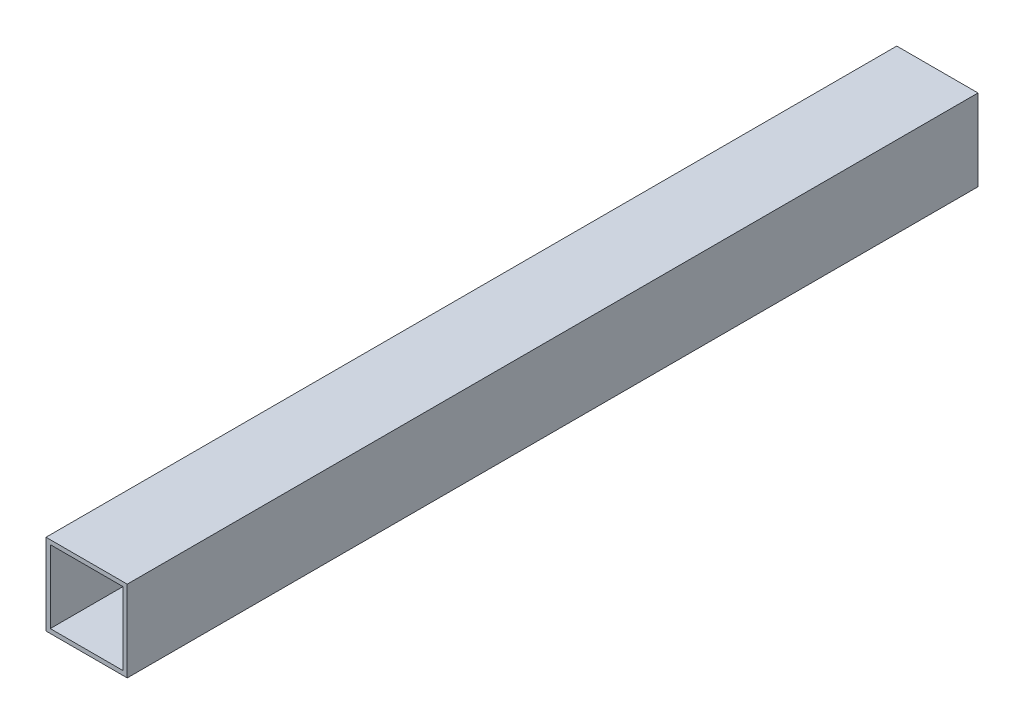
SolidWorks part; units mm, degrees
ref_plane "Front Plane" through (0, 0, 0) normal (0, 0, 1) x (1, 0, 0)
ref_plane "Top Plane" through (0, 0, 0) normal (0, 1, 0) x (1, 0, 0)
ref_plane "Right Plane" through (0, 0, 0) normal (1, 0, 0) x (0, 0, -1)
sketch "Sketch1" plane through (0, 0, 0) normal (0, 0, 1) x (1, 0, 0)
  line L0 (-15.8238, 8.2531) -> (1.2762, 8.2531)
  line L1 (-16.8238, 9.2531) -> (2.2762, 9.2531)
  line L2 (-16.8238, 9.2531) -> (-16.8238, -9.8469)
  line L3 (-16.8238, -9.8469) -> (2.2762, -9.8469)
  line L4 (2.2762, 9.2531) -> (2.2762, -9.8469)
  line L5 (1.2762, 8.2531) -> (1.2762, -8.8469)
  line L6 (-15.8238, -8.8469) -> (1.2762, -8.8469)
  line L7 (-15.8238, 8.2531) -> (-15.8238, -8.8469)
  dimension "D1" = 19.1
  dimension "D2" = 19.1
  dimension "D3" = 1
extrude "Boss-Extrude1" add sketch "Sketch1" along normal blind 200
